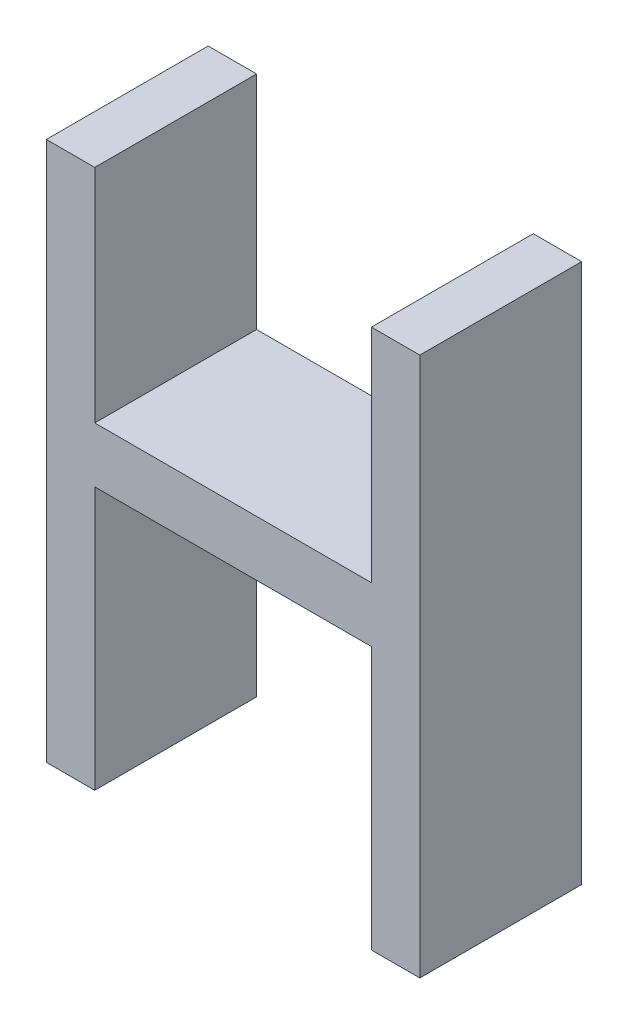
SolidWorks part; units mm, degrees
ref_plane "Plan de face" through (0, 0, 0) normal (0, 0, 1) x (1, 0, 0)
ref_plane "Plan de dessus" through (0, 0, 0) normal (0, 1, 0) x (1, 0, 0)
ref_plane "Plan de droite" through (0, 0, 0) normal (1, 0, 0) x (0, 0, -1)
sketch "Esquisse1" plane through (0, 0, 0) normal (0, 0, 1) x (1, 0, 0)
  text T0 "H" font "Century Gothic" height 5
extrude "Boss.-Extru.1" add sketch "Esquisse1" along normal blind 1.5
